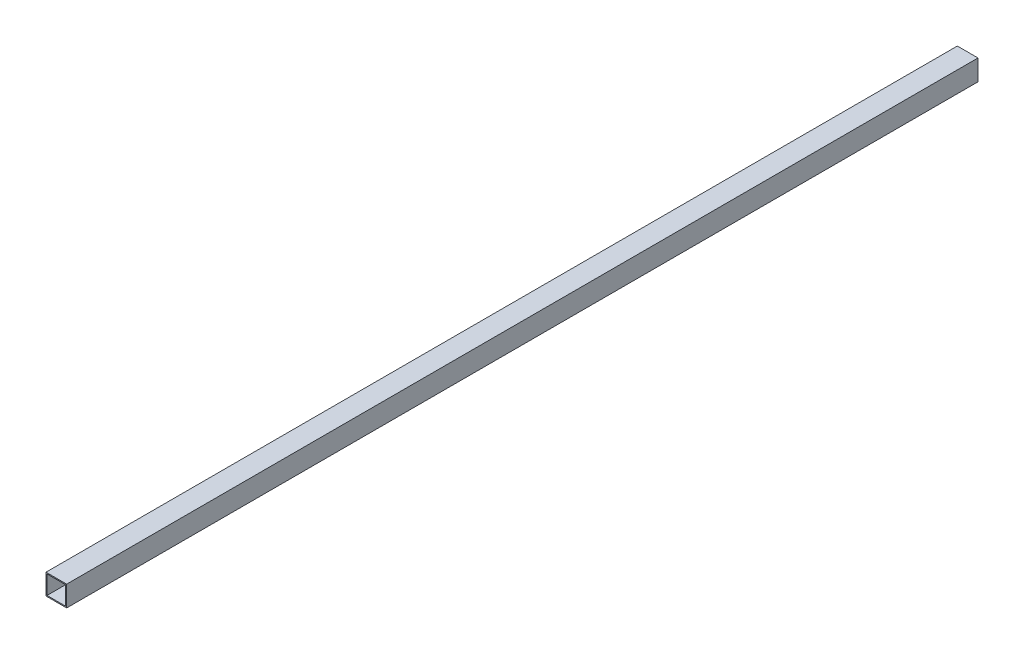
SolidWorks part; units mm, degrees
ref_plane "Front Plane" through (0, 0, 0) normal (0, 0, 1) x (1, 0, 0)
ref_plane "Top Plane" through (0, 0, 0) normal (0, 1, 0) x (1, 0, 0)
ref_plane "Right Plane" through (0, 0, 0) normal (1, 0, 0) x (0, 0, -1)
sketch "Sketch1" plane through (0, 0, 0) normal (0, 0, 1) x (1, 0, 0)
  line L5 (-15.875, 15.875) -> (15.875, 15.875)
  line L6 (-15.875, 15.875) -> (-15.875, -15.875)
  line L11 (-15.875, -15.875) -> (15.875, -15.875)
  line L12 (15.875, 15.875) -> (15.875, -15.875)
  line L13 (-15.875, 15.875) -> (15.875, -15.875) construction
  line L14 (-15.875, -15.875) -> (15.875, 15.875) construction
  line L15 (-14.2875, 14.2875) -> (14.2875, 14.2875)
  line L16 (-14.2875, 14.2875) -> (-14.2875, -14.2875)
  line L17 (-14.2875, -14.2875) -> (14.2875, -14.2875)
  line L18 (14.2875, 14.2875) -> (14.2875, -14.2875)
  line L19 (-14.2875, 14.2875) -> (14.2875, -14.2875) construction
  line L20 (-14.2875, -14.2875) -> (14.2875, 14.2875) construction
  point P0 (0, 0)
  point P6 (0, 0)
  dimension "D1" = 31.75
  dimension "D2" = 31.75
  dimension "D3" = 1.5875
extrude "Boss-Extrude1" add sketch "Sketch1" along normal blind 1400
